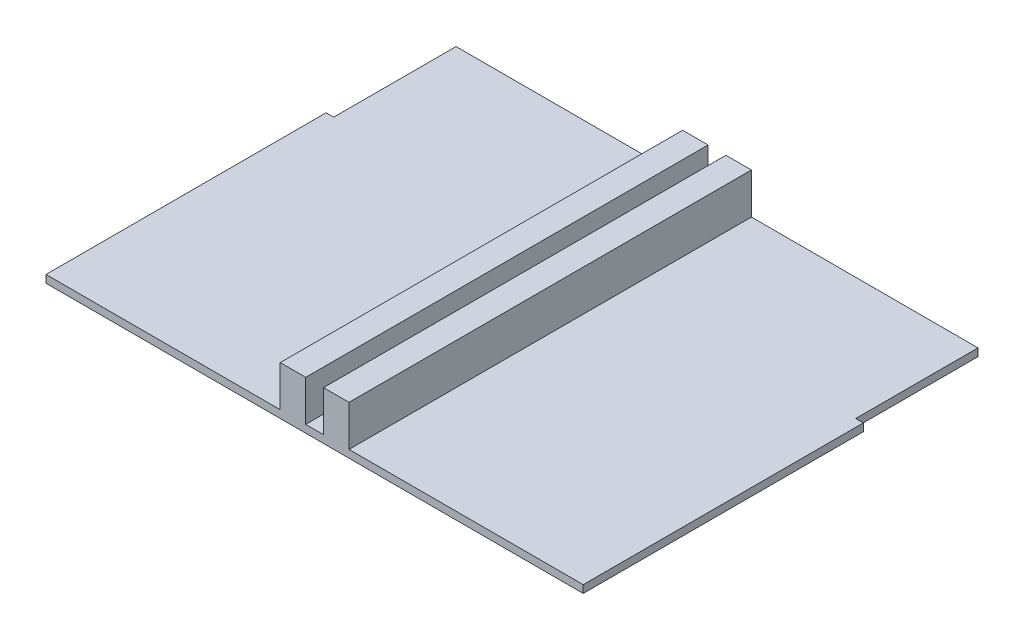
SolidWorks part; units mm, degrees
ref_plane "Front Plane" through (0, 0, 0) normal (0, 0, 1) x (1, 0, 0)
ref_plane "Top Plane" through (0, 0, 0) normal (0, 1, 0) x (1, 0, 0)
ref_plane "Right Plane" through (0, 0, 0) normal (1, 0, 0) x (0, 0, -1)
sketch "Sketch1" plane through (0, 0, 0) normal (0, 1, 0) x (1, 0, 0)
  line L0 (0, 15.8) -> (0, -15.8) construction
  line L1 (-10.55, -15.8) -> (10.55, -15.8)
  line L2 (-10.55, -15.8) -> (-10.55, 15.8)
  line L3 (-10.55, 15.8) -> (10.55, 15.8)
  line L4 (10.55, -15.8) -> (10.55, 15.8)
  line L5 (-10.55, -15.8) -> (10.55, 15.8) construction
  line L6 (-10.55, 15.8) -> (10.55, -15.8) construction
  line L7 (-10.25, 15.8) -> (-10.25, -15.8)
  line L8 (10.25, 15.8) -> (10.25, -15.8)
  line L9 (-10.55, 11) -> (10.55, 11)
  line L10 (-0.34, 15.8) -> (-0.34, 11)
  line L11 (0.34, 15.8) -> (0.34, 11)
  line L12 (-10.55, 0) -> (10.55, 0)
  line L13 (-10.54, -15.79) -> (-10.54, 15.79)
  line L14 (-10.54, 15.79) -> (10.54, 15.79)
  line L15 (10.54, -15.79) -> (10.54, 15.79)
  line L16 (-10.54, -15.79) -> (10.54, -15.79)
  line L17 (-0.35, 15.8) -> (-0.35, 11)
  line L18 (-10.55, 10.99) -> (10.55, 10.99)
  line L19 (0.35, 15.8) -> (0.35, 11)
  line L20 (-0.35, 11) -> (-0.35, 10.99)
  line L21 (0.35, 11) -> (0.35, 10.99)
  line L22 (-10.24, 15.8) -> (-10.24, -15.8)
  line L23 (10.24, 15.8) -> (10.24, -15.8)
  point P0 (0, 0)
  point P9 (-10.25, 15.8)
  point P14 (-10.55, 11)
  point P17 (-0.34, 15.8)
  dimension "D1" = 0.01
  dimension "D2" = 0.01
  dimension "D3" = 0.01
  dimension "D4" = 0.01
extrude "Boss-Extrude1" add sketch "Sketch1" along normal blind 0.3 contours L14 L22 L9 L17 | L23 L14 L19 L9 | L9 L22 L18 L20 | L23 L9 L21 L18 | L21 L9 L20 L18 | L23 L18 L22 L12 | L22 L18 L7 L12 | L18 L13 L12 L7 | L18 L8 L12 L15 | L18 L23 L12 L8
sketch "Sketch2" plane through (0, 0.3, 0) normal (0, 1, 0) x (1, 0, 0)
  line L0 (-10.54, 0) -> (10.54, 0) construction
  line L1 (-0.35, 15.79) -> (-1.35, 15.79)
  line L2 (-0.35, 15.79) -> (-0.35, 0)
  line L3 (-0.35, 0) -> (-1.35, 0)
  line L4 (-1.35, 15.79) -> (-1.35, 0)
  line L5 (0, 11) -> (0, 0) construction
  line L6 (-0.35, 11) -> (0.35, 11) construction
  line L7 (0.35, 0) -> (1.35, 0)
  line L8 (1.35, 15.79) -> (1.35, 0)
  line L9 (0.35, 15.79) -> (1.35, 15.79)
  line L10 (0.35, 15.79) -> (0.35, 0)
extrude "Boss-Extrude2" add sketch "Sketch2" along normal blind 1.6
